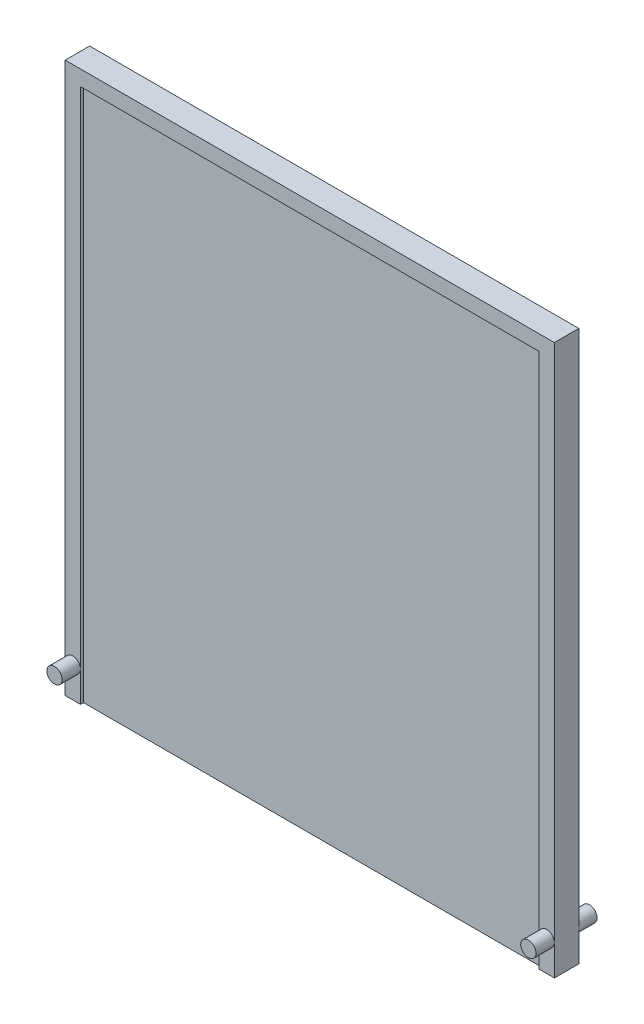
SolidWorks part; units mm, degrees
ref_plane "前视基准面" through (0, 0, 0) normal (0, 0, 1) x (1, 0, 0)
ref_plane "上视基准面" through (0, 0, 0) normal (0, 1, 0) x (1, 0, 0)
ref_plane "右视基准面" through (0, 0, 0) normal (1, 0, 0) x (0, 0, -1)
sketch "草图1" plane through (0, 0, 0) normal (0, 0, 1) x (1, 0, 0)
  line L1 (-80, -90) -> (80, -90)
  line L2 (-80, -90) -> (-80, 90)
  line L3 (-80, 90) -> (80, 90)
  line L4 (80, -90) -> (80, 90)
  line L5 (-80, -90) -> (80, 90) construction
  line L6 (-80, 90) -> (80, -90) construction
  point P0 (0, 0)
  dimension "D1" = 180
  dimension "D2" = 160
extrude "凸台-拉伸1" add sketch "草图1" along normal mid plane 8
sketch "草图2" plane through (0, 0, 4) normal (0, 0, 1) x (1, 0, 0)
  line L0 (0, 0) -> (0, 10) construction
  line L2 (-75, -90) -> (-75, 85)
  line L3 (-75, 85) -> (75, 85)
  line L4 (75, -90) -> (75, 85)
  line L5 (0, -90) -> (0, 0) construction
  line L6 (80, 90) -> (-80, 90) construction
  line L8 (-80, -90) -> (80, -90) construction
  line L9 (-75, -90) -> (75, -90)
  point P0 (7.027, 3.6999)
  point P2 (75.5705, -90)
  point P13 (-75, -88.9213)
  dimension "D1" = 5
  dimension "D3" = 10
  dimension "D4" = 150
extrude "切除-拉伸1" cut sketch "草图2" against normal blind 1
sketch "草图3" plane through (0, 0, 0) normal (0, 0, 1) x (1, 0, 0)
  line L0 (-77.5, -90) -> (-77.5, -80) construction
  line L1 (-80, -90) -> (-75, -90) construction
  line L2 (0, -90) -> (0, -27.5045) construction
  line L3 (-75, -90) -> (75, -90) construction
  circle A0 centre (-77.5, -80) radius 2.5
  circle A1 centre (77.5, -80) radius 2.5
  dimension "D1" = 5
  dimension "D2" = 10
extrude "凸台-拉伸2" add sketch "草图3" along normal mid plane 20
